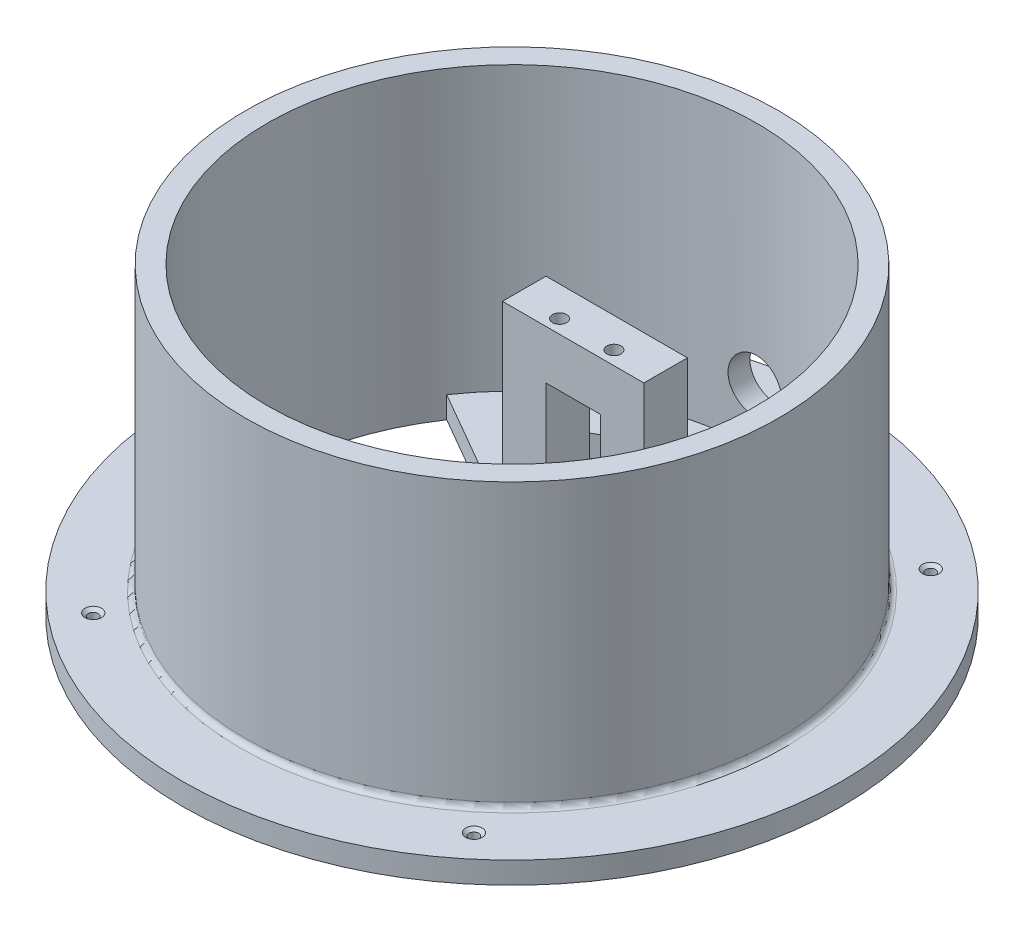
SolidWorks part; units mm, degrees
ref_plane "Front Plane" through (0, 0, 0) normal (0, 0, 1) x (1, 0, 0)
ref_plane "Top Plane" through (0, 0, 0) normal (0, 1, 0) x (1, 0, 0)
ref_plane "Right Plane" through (0, 0, 0) normal (1, 0, 0) x (0, 0, -1)
sketch "Sketch1" plane through (0, 0, 0) normal (0, 1, 0) x (1, 0, 0)
  circle A0 centre (0, 0) radius 60.625
  circle A1 centre (0, 0) radius 45
  dimension "D1" = 90
  dimension "D2" = 121.25
extrude "Boss-Extrude1" add sketch "Sketch1" along normal blind 4
sketch "Sketch2" plane through (0, 4, 0) normal (0, 1, 0) x (1, 0, 0)
  circle A0 centre (0, 0) radius 45 construction
  circle A1 centre (0, 0) radius 45
  circle A2 centre (0, 0) radius 49
  dimension "D1" = 4
extrude "Boss-Extrude2" add sketch "Sketch2" along normal blind 52
sketch "Sketch3" plane through (0, 0, 0) normal (1, 0, 0) x (0, 0, -1)
  line L0 (-45, 38) -> (-31.75, 38)
  line L1 (-31.75, 38) -> (-31.75, 30)
  line L2 (-31.75, 30) -> (-45, 30)
  line L4 (-45, 38) -> (-45, 16.75)
  line L5 (-31.75, 30) -> (-45, 16.75)
  line L6 (-60.625, 0) -> (60.625, 0) construction
  line L7 (19.25, 0) -> (11.25, 0)
  line L8 (19.25, 0) -> (19.25, 38)
  line L9 (19.25, 38) -> (11.25, 38)
  line L10 (11.25, 0) -> (11.25, 38)
  line L11 (45, 56) -> (-45, 56) construction
  line L12 (0, 56) -> (0, 4) construction
  dimension "D1" = 8
  dimension "D2" = 18
  dimension "D3" = 43
  dimension "D5" = 45
  dimension "D6" = 18
  dimension "D7" = 8
  dimension "D8" = 11.25
extrude "Boss-Extrude3" add sketch "Sketch3" along normal mid plane 26 contours L5 L4 L0 L1 | L10 L9 L8 L7
sketch "Sketch5" plane through (0, 0, -11.25) normal (0, 0, 1) x (1, 0, 0)
  line L0 (13, 38) -> (-13, 38) construction
  line L1 (-5, 5) -> (5, 5)
  line L2 (-5, 5) -> (-5, 29)
  line L3 (-5, 29) -> (5, 29)
  line L4 (5, 5) -> (5, 29)
  line L5 (-5, 5) -> (5, 29) construction
  line L6 (-5, 29) -> (5, 5) construction
  line L7 (13, 0) -> (-13, 0) construction
  point P0 (0, 17)
  point P11 (0, 5)
  dimension "D1" = 10
  dimension "D2" = 9
  dimension "D3" = 5
extrude "Cut-Extrude1" cut sketch "Sketch5" against normal blind 23
sketch "Sketch6" plane through (0, 0, -11.25) normal (0, 0, 1) x (1, 0, 0)
  line L0 (13, 0) -> (-13, 0) construction
  circle A0 centre (0, 14) radius 5
  dimension "D1" = 10
  dimension "D2" = 14
extrude "Cut-Extrude2" cut sketch "Sketch6" against normal blind 60
sketch "Sketch7" plane through (0, 38, 0) normal (0, 1, 0) x (1, 0, 0)
  line L0 (-5, -34.25) -> (5, -34.25) construction
  line L1 (-5, 13.75) -> (5, 13.75) construction
  line L2 (13, -31.75) -> (-13, -31.75) construction
  circle A0 centre (-5, 13.75) radius 1.3
  circle A1 centre (5, 13.75) radius 1.3
  circle A2 centre (5, -34.25) radius 1.3
  circle A3 centre (-5, -34.25) radius 1.3
  dimension "D1" = 2.6
  dimension "D2" = 5
  dimension "D3" = 48
  dimension "D4" = 2.5
  dimension "D5" = 10
  dimension "D6" = 10
extrude "Cut-Extrude3" cut sketch "Sketch7" against normal blind 7.2
sketch "Sketch8" plane through (0, 0, 0) normal (0, -1, 0) x (1, 0, 0)
  line L0 (13, -11.25) -> (-13, -11.25) construction
  line L1 (13, -11.25) -> (-13, -11.25)
  line L2 (-13, -11.25) -> (-37.2484, -25.2498)
  line L3 (0, 0) -> (0, -29.9727) construction
  line L4 (13, -11.25) -> (37.2484, -25.2498)
  line L5 (19.5167, -24.25) -> (24.9065, -27.3618)
  line L6 (-19.5167, -24.25) -> (-24.9065, -27.3618)
  line L8 (-19.5167, -24.25) -> (19.5167, -24.25)
  line L9 (13, -19.25) -> (-13, -19.25) construction
  line L10 (-10.8564, -19.25) -> (-24.9065, -27.3618) construction
  line L11 (10.8564, -19.25) -> (-10.8564, -19.25) construction
  line L12 (10.8564, -19.25) -> (24.9065, -27.3618) construction
  circle A0 centre (0, 0) radius 45 construction
  arc A1 (-37.2484, -25.2498) -> (37.2484, -25.2498) centre (0, 0) ccw
  arc A2 (-24.9065, -27.3618) -> (24.9065, -27.3618) centre (0, 0) ccw
  dimension "D1" = 60
  dimension "D3" = 5
  dimension "D2" = 8
extrude "Boss-Extrude4" add sketch "Sketch8" against normal blind 4
sketch "Sketch9" plane through (0, 4, 0) normal (0, 1, 0) x (1, 0, 0)
  line L1 (-35, -42) -> (35, -42) construction
  line L2 (-35, -42) -> (-35, 42) construction
  line L3 (-35, 42) -> (35, 42) construction
  line L4 (35, -42) -> (35, 42) construction
  line L5 (-35, -42) -> (35, 42) construction
  line L6 (-35, 42) -> (35, -42) construction
  point P0 (0, 0)
  dimension "D1" = 70
  dimension "D2" = 84
hole_wizard "CSK for #0 Flat Head Machine Screw (100)1" positions "Sketch10" profile "Sketch11" countersink size "#0" standard "ANSI Inch" end condition through all
sketch "Sketch10" plane through (0, 4, 0) normal (0, 1, 0) x (1, 0, 0)
  point P0 (-35, 42)
  point P3 (35, 42)
  point P6 (35, -42)
  point P9 (-35, -42)
  point P12 (-35, -42)
sketch "Sketch11" plane through (-35, 4, -42) normal (1, 0, 0) x (0, 0, 1)
  line L0 (0, 0) -> (0, 4)
  line L1 (0, 4) -> (0.889, 4)
  line L2 (0.889, 4) -> (0.889, 0.5222)
  line L3 (0.889, 0.5222) -> (1.5113, 0)
  line L5 (1.5113, 0) -> (0, 0)
  line L6 (-0.889, 0.5222) -> (-1.5113, 0) construction
  line L11 (0, -6.35) -> (0, 107.95) construction
  dimension "Thru Hole Dia." = 1.778
  dimension "Thru Hole Depth" = 4
  dimension "Near C'Sink Dia." = 3.0226
  dimension "Near C'Sink Angle" = 100
fillet "Fillet1" radius 1 1 edges at (0, 4, 49)
sketch "Sketch12" plane through (0, 0, 0) normal (0, -1, 0) x (1, 0, 0)
  point P0 (0, 0)
  point P3 (0, 0)
